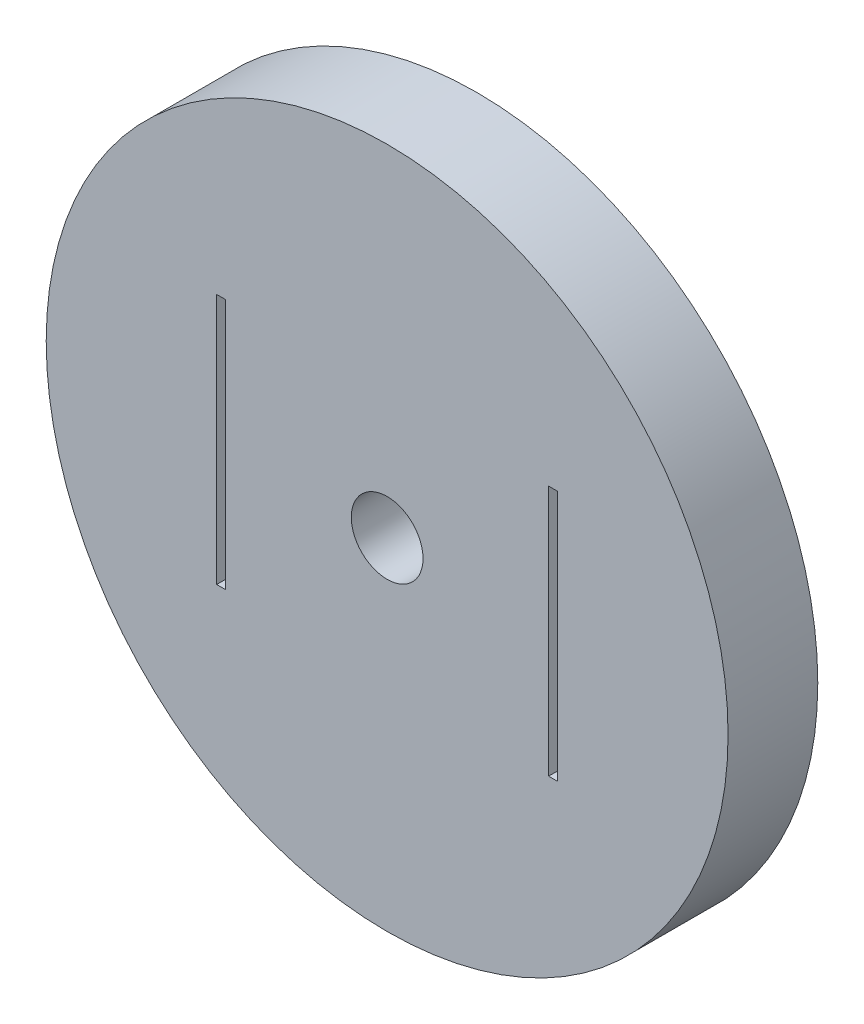
SolidWorks part; units mm, degrees
ref_plane "Front Plane" through (0, 0, 0) normal (0, 0, 1) x (1, 0, 0)
ref_plane "Top Plane" through (0, 0, 0) normal (0, 1, 0) x (1, 0, 0)
ref_plane "Right Plane" through (0, 0, 0) normal (1, 0, 0) x (0, 0, -1)
sketch "Sketch1" plane through (0, 0, 0) normal (0, 0, 1) x (1, 0, 0)
  line L0 (0, 10.3237) -> (0, -11.9962) construction
  line L1 (-9.5, 7) -> (-9, 7)
  line L2 (-9.5, 7) -> (-9.5, -7)
  line L3 (-9.5, -7) -> (-9, -7)
  line L4 (-9, 7) -> (-9, -7)
  line L5 (9, 7) -> (9, -7)
  line L6 (9.5, -7) -> (9, -7)
  line L7 (9.5, 7) -> (9.5, -7)
  line L8 (9.5, 7) -> (9, 7)
  circle A0 centre (0, 0) radius 19
  circle A1 centre (0, 0) radius 2
  dimension "D1" = 4
  dimension "D2" = 38
  dimension "D3" = 0.5
  dimension "D4" = 9
  dimension "D5" = 7
  dimension "D6" = 7
extrude "Boss-Extrude1" add sketch "Sketch1" along normal blind 5
sketch "Sketch3" plane through (0, 0, 0) normal (0, 1, 0) x (1, 0, 0)
  line L0 (-14.5, 6.5) -> (-14.5, 0) construction
  line L1 (19, 0) -> (-19, 0) construction
  line L2 (-16.5, 6.5) -> (-16.5, 0)
  line L3 (-16.5, 0) -> (-14.5, 0)
  line L4 (-14.5, 0) -> (-14.5, 8.5)
  line L5 (-19, 0) -> (-19, -5) construction
  circle A0 centre (-14.5, 6.5) radius 2 construction
  arc A1 (-16.5, 6.5) -> (-14.5, 8.5) centre (-14.5, 6.5) cw
  dimension "D1" = 4
  dimension "D2" = 4.5
  dimension "D3" = 8.5
revolve "Revolve1" add sketch "Sketch3" angle 360 about L0
